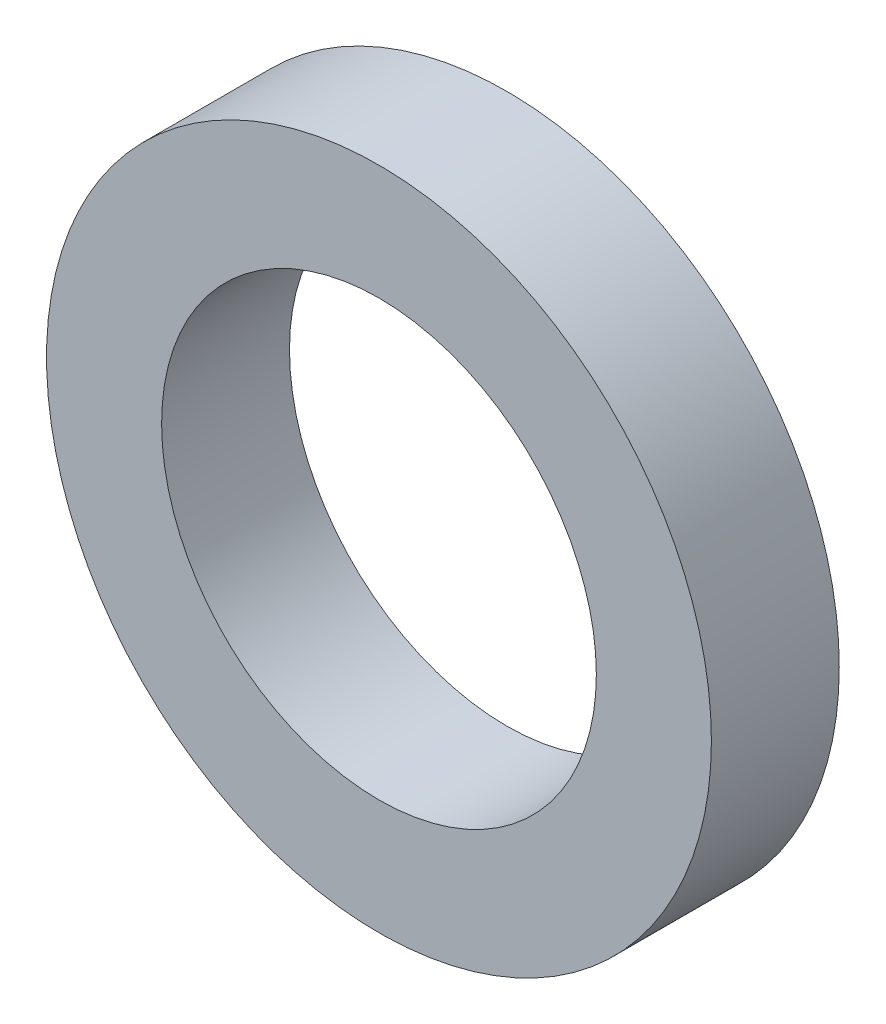
SolidWorks part; units mm, degrees
ref_plane "Спереди" through (0, 0, 0) normal (0, 0, 1) x (1, 0, 0)
ref_plane "Сверху" through (0, 0, 0) normal (0, 1, 0) x (1, 0, 0)
ref_plane "Справа" through (0, 0, 0) normal (1, 0, 0) x (0, 0, -1)
sketch "Эскиз1" plane through (0, 0, 0) normal (0, 0, 1) x (1, 0, 0)
  circle A0 centre (0, 0) radius 13
  circle A1 centre (0, 0) radius 8.5
  dimension "D1" = 17
  dimension "D2" = 26
extrude "Бобышка-Вытянуть1" add sketch "Эскиз1" along normal blind 5
